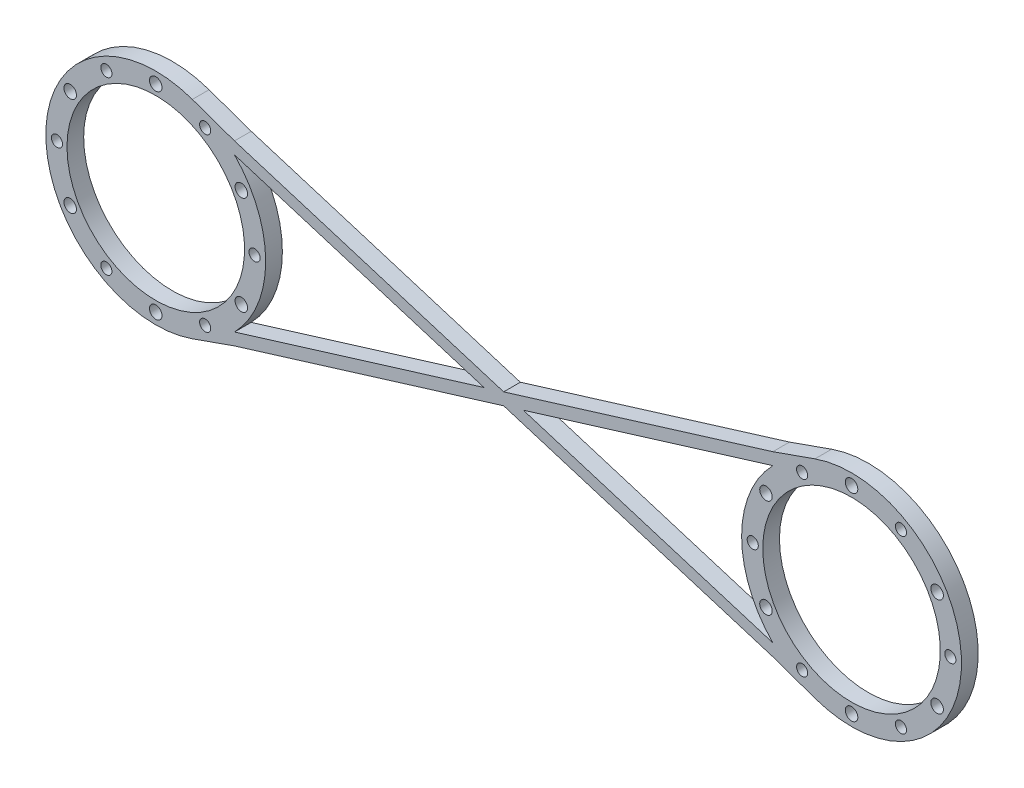
SolidWorks part; units mm, degrees
ref_plane "前视基准面" through (0, 0, 0) normal (0, 0, 1) x (1, 0, 0)
ref_plane "上视基准面" through (0, 0, 0) normal (0, 1, 0) x (1, 0, 0)
ref_plane "右视基准面" through (0, 0, 0) normal (1, 0, 0) x (0, 0, -1)
sketch "草图1" plane through (0, 0, 0) normal (0, 0, 1) x (1, 0, 0)
  line L0 (0, 0) -> (28, 0)
  line L1 (28, 0) -> (28, -56)
  line L2 (28, -56) -> (-28, -56)
  line L3 (-28, -56) -> (-28, 0)
  line L4 (-28, 0) -> (0, 0)
extrude "凸台-拉伸1" add sketch "草图1" along normal blind 8
sketch "草图2" plane through (0, 0, 0) normal (0, 0, -1) x (-1, 0, 0)
  circle A0 centre (-23.55, -4.45) radius 2.5
  circle A1 centre (23.55, -4.45) radius 2.5
  circle A2 centre (23.55, -51.55) radius 2.5
  circle A3 centre (-23.55, -51.55) radius 2.5
extrude "切除-拉伸1" cut sketch "草图2" against normal blind 8
sketch "草图3" plane through (0, 0, 0) normal (0, 0, -1) x (-1, 0, 0)
  circle A0 centre (0, -28) radius 15
extrude "切除-拉伸3" cut sketch "草图3" against normal blind 8
sketch "草图4" plane through (0, 0, 0) normal (0, 0, -1) x (-1, 0, 0)
  circle A0 centre (0, -28) radius 25
extrude "凸台-拉伸2" add sketch "草图4" along normal blind 8
sketch "草图6" plane through (0, 0, -8) normal (0, 0, -1) x (-1, 0, 0)
  circle A0 centre (0, -28) radius 15
extrude "切除-拉伸6" cut sketch "草图6" against normal blind 8
sketch "草图9" plane through (0, 0, -8) normal (0, 0, -1) x (-1, 0, 0)
  circle A0 centre (0, -28) radius 39.5
extrude "凸台-拉伸3" add sketch "草图9" along normal blind 8
sketch "草图10" plane through (0, 0, -16) normal (0, 0, -1) x (-1, 0, 0)
  circle A0 centre (0, -28) radius 15
extrude "切除-拉伸7" cut sketch "草图10" against normal blind 8
fillet "圆角3" radius 5 1 edges at (-28, 0, 4)
fillet "圆角4" radius 5 1 edges at (28, 0, 4)
fillet "圆角5" radius 5 1 edges at (28, -56, 4)
fillet "圆角6" radius 5 1 edges at (-28, -56, 4)
sketch "草图11" plane through (0, 0, -16) normal (0, 0, -1) x (-1, 0, 0)
  circle A0 centre (0, -28) radius 20
extrude "切除-拉伸9" cut sketch "草图11" against normal blind 188
sketch "草图12" plane through (0, 0, -16) normal (0, 0, -1) x (-1, 0, 0)
  circle A0 centre (0, 7.5) radius 2.25
  circle A1 centre (25.1023, -2.8977) radius 2.25
  circle A2 centre (35.5, -28) radius 2.25
  circle A3 centre (25.1023, -53.1023) radius 2.25
  circle A4 centre (0, -63.5) radius 2.25
  circle A5 centre (-25.1023, -53.1023) radius 2.25
  circle A6 centre (-35.5, -28) radius 2.25
  circle A7 centre (-25.1023, -2.8977) radius 2.25
  circle A8 centre (13.5853, 4.7977) radius 2
  circle A9 centre (32.7977, -14.4147) radius 2
  circle A10 centre (32.7977, -41.5853) radius 2
  circle A11 centre (13.5853, -60.7977) radius 2
  circle A12 centre (-13.5853, -60.7977) radius 2
  circle A13 centre (-32.7977, -41.5853) radius 2
  circle A14 centre (-32.7977, -14.4147) radius 2
  circle A15 centre (-13.5853, 4.7977) radius 2
extrude "切除-拉伸10" cut sketch "草图12" against normal blind 9
sketch "草图13" plane through (0, 0, 8) normal (0, 0, 1) x (1, 0, 0)
  circle A0 centre (-7.5178, -22.2915) radius 54.473
extrude "切除-拉伸11" cut sketch "草图13" against normal blind 2
sketch "草图14" plane through (0, 0, -16) normal (0, 0, -1) x (-1, 0, 0)
  circle A0 centre (0.9942, -28.0217) radius 59.1589
extrude "切除-拉伸12" cut sketch "草图14" against normal blind 2
sketch "草图15" plane through (0, 0, 6) normal (0, 0, 1) x (1, 0, 0)
  circle A0 centre (21.3873, -13.1283) radius 97.5442
extrude "切除-拉伸13" cut sketch "草图15" against normal up to surface (14 mm away) up to face at (-15.5853, 4.7977, -8)
sketch "草图16" plane through (0, 0, -14) normal (0, 0, -1) x (-1, 0, 0)
  circle A0 centre (0, -28) radius 31.9
extrude "切除-拉伸14" cut sketch "草图16" against normal blind 10
sketch "草图17" plane through (0, 0, -14) normal (0, 0, -1) x (-1, 0, 0)
  line L0 (0, -65.75) -> (0, -61.25)
  line L1 (0, -61.25) -> (2.25, -61.25)
  line L2 (2.25, -61.25) -> (2.25, -65.75)
  line L3 (2.25, -65.75) -> (0, -65.75)
  circle A0 centre (0, -63.5) radius 2.25 construction
extrude "凸台-拉伸4" add sketch "草图17" against normal blind 6
sketch "草图18" plane through (0, 0, 0) normal (1, 0, 0) x (0, 0, -1)
  line L1 (14, -61.25) -> (8, -61.25)
  line L2 (14, -61.25) -> (14, -65.75)
  line L3 (14, -65.75) -> (8, -65.75)
  line L4 (8, -61.25) -> (8, -65.75)
extrude "凸台-拉伸5" add sketch "草图18" along normal blind 200
sketch "草图19" plane through (0, 0, -14) normal (0, 0, -1) x (-1, 0, 0)
  line L0 (-200, -65.75) -> (-200, -67.5)
  line L1 (-200, -67.5) -> (-11.625, -67.5)
  line L2 (-11.625, -67.5) -> (0, -67.5)
  line L3 (0, -67.5) -> (0, -65.75)
  line L4 (0, -65.75) -> (-11.627, -65.75)
  line L5 (-11.627, -65.75) -> (-200, -65.75)
  arc A0 (-11.627, -65.75) -> (-21.3234, -61.25) centre (0, -28) ccw construction
extrude "凸台-拉伸6" add sketch "草图19" against normal blind 6
sketch "草图21" plane through (0, 0, -14) normal (0, 0, -1) x (-1, 0, 0)
  line L0 (-200, -61.25) -> (-200, -59.9)
  line L1 (-200, -59.9) -> (0, -59.9)
  line L2 (0, -59.9) -> (0, -61.25)
  line L3 (0, -61.25) -> (-200, -61.25)
  circle A0 centre (0, -28) radius 31.9 construction
extrude "凸台-拉伸7" add sketch "草图21" against normal blind 6
sketch "草图22" plane through (0, 0, -14) normal (0, 0, -1) x (-1, 0, 0)
  circle A0 centre (-223.2946, -28) radius 39.5
extrude "凸台-拉伸8" add sketch "草图22" against normal blind 6 separate body
sketch "草图23" plane through (0, 0, -14) normal (0, 0, -1) x (-1, 0, 0)
  circle A0 centre (-223.2946, -28) radius 31.9
extrude "切除-拉伸15" cut sketch "草图23" against normal blind 6
sketch "草图26" plane through (0, 0, -14) normal (0, 0, -1) x (-1, 0, 0)
  line L0 (-200, -59.9) -> (-223.2946, -59.9)
  line L1 (-223.2946, -59.9) -> (-223.2946, -67.5)
  line L2 (-223.2946, -67.5) -> (-200, -67.5)
  line L3 (-200, -67.5) -> (-200, -59.9)
  circle A0 centre (-223.2946, -28) radius 31.9 construction
  circle A1 centre (-223.2946, -28) radius 39.5 construction
extrude "凸台-拉伸9" add sketch "草图26" against normal blind 6
sketch "草图27" plane through (0, 0, -14) normal (0, 0, -1) x (-1, 0, 0)
  circle A0 centre (-223.2946, 7.5) radius 2.25
  circle A1 centre (-198.1923, -2.8977) radius 2.25
  circle A2 centre (-187.7946, -28) radius 2.25
  circle A3 centre (-198.1923, -53.1023) radius 2.25
  circle A4 centre (-223.2946, -63.5) radius 2.25
  circle A5 centre (-248.3969, -53.1023) radius 2.25
  circle A6 centre (-258.7946, -28) radius 2.25
  circle A7 centre (-248.3969, -2.8977) radius 2.25
  circle A8 centre (-209.7094, 4.7977) radius 2
  circle A9 centre (-190.4969, -14.4147) radius 2
  circle A10 centre (-190.4969, -41.5853) radius 2
  circle A11 centre (-209.7094, -60.7977) radius 2
  circle A12 centre (-236.8799, -60.7977) radius 2
  circle A13 centre (-256.0924, -41.5853) radius 2
  circle A14 centre (-256.0924, -14.4147) radius 2
  circle A15 centre (-236.8799, 4.7977) radius 2
extrude "切除-拉伸16" cut sketch "草图27" against normal blind 6
sketch "草图28" plane through (0, 0, -14) normal (0, 0, -1) x (-1, 0, 0)
  line L4 (-223.2946, 5.25) -> (-223.2946, 7.5)
  line L5 (-223.2946, 7.5) -> (-223.2946, 9.75)
  line L6 (-223.2946, 9.75) -> (-221.0446, 9.75)
  line L7 (-221.0446, 9.75) -> (-221.0446, 5.25)
  line L8 (-221.0446, 5.25) -> (-223.2946, 5.25)
  circle A4 centre (-223.2946, 7.5) radius 2.25 construction
extrude "凸台-拉伸10" add sketch "草图28" against normal blind 6
sketch "草图29" plane through (223.2946, 0, 0) normal (1, 0, 0) x (0, 0, -1)
  line L1 (14, 9.75) -> (8, 9.75)
  line L2 (14, 9.75) -> (14, 5.25)
  line L3 (14, 5.25) -> (8, 5.25)
  line L4 (8, 9.75) -> (8, 5.25)
extrude "凸台-拉伸11" add sketch "草图29" against normal blind 227
sketch "草图30" plane through (0, 0, -14) normal (0, 0, -1) x (-1, 0, 0)
  line L1 (-11.627, 11.5) -> (0, 11.5)
  line L2 (0, 11.5) -> (0, 9.75)
  line L3 (0, 9.75) -> (-223.2946, 9.75)
  line L4 (-223.2946, 9.75) -> (-223.2946, 11.5)
  line L5 (-223.2946, 11.5) -> (-11.627, 11.5)
  arc A0 (0, -67.5) -> (-11.627, 9.75) centre (0, -28) ccw construction
  arc A1 (-211.6676, 9.75) -> (-223.2946, -67.5) centre (-223.2946, -28) ccw construction
extrude "凸台-拉伸12" add sketch "草图30" against normal blind 6
sketch "草图31" plane through (0, 0, -14) normal (0, 0, -1) x (-1, 0, 0)
  line L0 (-201.9712, 5.25) -> (-201.9712, 3.9)
  line L1 (-201.9712, 3.9) -> (-9.5197, 3.9)
  line L2 (-9.5197, 3.9) -> (-9.5197, 5.25)
  line L3 (-9.5197, 5.25) -> (-201.9712, 5.25)
extrude "凸台-拉伸13" add sketch "草图31" against normal blind 6
sketch "草图32" plane through (0, 0, -14) normal (0, 0, -1) x (-1, 0, 0)
  circle A0 centre (-13.5853, 4.7977) radius 2
extrude "切除-拉伸17" cut sketch "草图32" against normal blind 6
sketch "草图33" plane through (0, 0, -14) normal (0, 0, -1) x (-1, 0, 0)
  circle A0 centre (0, 7.5) radius 2.25
extrude "切除-拉伸18" cut sketch "草图33" against normal blind 6
sketch "草图34" plane through (0, 0, -14) normal (0, 0, -1) x (-1, 0, 0)
  circle A0 centre (-13.5853, -60.7977) radius 2
extrude "切除-拉伸19" cut sketch "草图34" against normal blind 6
sketch "草图35" plane through (0, 0, -14) normal (0, 0, -1) x (-1, 0, 0)
  circle A0 centre (0, -63.5) radius 2.25
extrude "切除-拉伸20" cut sketch "草图35" against normal blind 6
sketch "草图36" plane through (0, 0, -14) normal (0, 0, -1) x (-1, 0, 0)
  circle A0 centre (-223.2946, 7.5) radius 2.25
  circle A1 centre (-209.7094, 4.7977) radius 2
extrude "切除-拉伸21" cut sketch "草图36" against normal blind 6
sketch "草图37" plane through (0, 0, -14) normal (0, 0, -1) x (-1, 0, 0)
  circle A0 centre (26.7054, -28) radius 39.5
extrude "凸台-拉伸14" add sketch "草图37" against normal blind 6 contours A0
sketch "草图38" plane through (0, 0, -14) normal (0, 0, -1) x (-1, 0, 0)
  circle A0 centre (26.7054, -28) radius 31.9
extrude "切除-拉伸22" cut sketch "草图38" against normal blind 6
sketch "草图39" plane through (0, 0, -14) normal (0, 0, -1) x (-1, 0, 0)
  line L0 (13.3527, 9.1747) -> (-4.9924, 19.1101)
  line L1 (-4.9924, 19.1101) -> (-56.4941, 19.1101)
  line L2 (-56.4941, 19.1101) -> (-56.4941, -75.9838)
  line L3 (-56.4941, -75.9838) -> (13.3527, -75.9838)
  line L4 (13.3527, -75.9838) -> (13.3527, -65.1747)
  arc A0 (13.3527, -65.1747) -> (13.3527, 9.1747) centre (26.7054, -28) cw
  arc A1 (13.3527, -65.1747) -> (13.3527, 9.1747) centre (26.7054, -28) ccw construction
extrude "切除-拉伸23" cut sketch "草图39" against normal blind 6
sketch "草图40" plane through (0, 0, -14) normal (0, 0, -1) x (-1, 0, 0)
  line L1 (-56.4941, 3.9) -> (26.7054, 3.9)
  line L2 (-56.4941, 3.9) -> (-56.4941, 11.5)
  line L3 (-56.4941, 11.5) -> (26.7054, 11.5)
  line L4 (26.7054, 3.9) -> (26.7054, 11.5)
  circle A0 centre (26.7054, -28) radius 39.5 construction
extrude "凸台-拉伸15" add sketch "草图40" against normal blind 6
sketch "草图41" plane through (0, 0, -14) normal (0, 0, -1) x (-1, 0, 0)
  line L1 (-56.4941, -59.9) -> (26.7054, -59.9)
  line L2 (-56.4941, -59.9) -> (-56.4941, -67.5)
  line L3 (-56.4941, -67.5) -> (26.7054, -67.5)
  line L4 (26.7054, -59.9) -> (26.7054, -67.5)
  arc A0 (3.4107, 3.9) -> (26.7054, 11.5) centre (26.7054, -28) ccw construction
extrude "凸台-拉伸16" add sketch "草图41" against normal blind 6
sketch "草图42" plane through (0, 0, -14) normal (0, 0, -1) x (-1, 0, 0)
  circle A0 centre (26.7054, -63.5) radius 2.25
  circle A1 centre (1.6031, -53.1023) radius 2.25
  circle A2 centre (-8.7946, -28) radius 2.25
  circle A3 centre (1.6031, -2.8977) radius 2.25
  circle A4 centre (26.7054, 7.5) radius 2.25
  circle A5 centre (51.8077, -2.8977) radius 2.25
  circle A6 centre (62.2054, -28) radius 2.25
  circle A7 centre (51.8077, -53.1023) radius 2.25
extrude "切除-拉伸24" cut sketch "草图42" against normal blind 6
sketch "草图43" plane through (0, 0, -14) normal (0, 0, -1) x (-1, 0, 0)
  circle A1 centre (13.1201, -60.7977) radius 2
  circle A2 centre (-6.0924, -41.5853) radius 2
  circle A3 centre (-6.0924, -14.4147) radius 2
  circle A4 centre (13.1201, 4.7977) radius 2
  circle A5 centre (40.2906, 4.7977) radius 2
  circle A6 centre (59.5031, -14.4147) radius 2
  circle A7 centre (59.5031, -41.5853) radius 2
  circle A8 centre (40.2906, -60.7977) radius 2
extrude "切除-拉伸25" cut sketch "草图43" against normal blind 6
sketch "草图45" plane through (0, 0, -14) normal (0, 0, -1) x (-1, 0, 0)
  line L0 (3.4107, 3.9) -> (-1.5893, 3.9)
  line L1 (-200, 3.9) -> (3.4107, 3.9) construction
  line L2 (3.4107, 3.9) -> (-0.3265, -0.2075)
  line L3 (-200, -59.9) -> (-195, -59.9)
  line L4 (3.4107, -59.9) -> (-200, -59.9) construction
  line L5 (-195, -59.9) -> (-1.5893, -0.438)
  line L6 (-1.5893, 3.9) -> (-195, -55.562)
  line L7 (-0.3265, -0.2075) -> (-1.5893, -0.438)
  line L8 (-200, -59.9) -> (-196.0531, -55.562)
  line L9 (-196.0531, -55.562) -> (-195, -55.562)
  arc A0 (3.4107, 3.9) -> (3.4107, -59.9) centre (26.7054, -28) ccw construction
  arc A1 (-200, -59.9) -> (-200, 3.9) centre (-223.2946, -28) ccw construction
extrude "凸台-拉伸17" add sketch "草图45" against normal blind 6
sketch "草图46" plane through (0, 0, -14) normal (0, 0, -1) x (-1, 0, 0)
  line L0 (3.4107, -59.9) -> (-1.5893, -59.9)
  line L1 (3.4107, -59.9) -> (-195, -59.9) construction
  line L2 (-1.5893, -55.562) -> (3.4107, -56.6542)
  line L3 (-200, 3.9) -> (-195, 3.9)
  line L4 (-200, 3.9) -> (-1.5893, 3.9) construction
  line L6 (-195, 3.9) -> (-1.5893, -55.562)
  line L7 (3.4107, -56.6542) -> (3.4107, -59.9)
  line L8 (-1.5893, -59.9) -> (-195, -0.438)
  line L9 (-195, -0.438) -> (-198.2205, 0.6383)
  line L10 (-198.2205, 0.6383) -> (-200, 3.9)
  arc A0 (-1.5893, -0.438) -> (3.4107, -59.9) centre (26.7054, -28) ccw construction
  arc A1 (-195, -55.562) -> (-200, 3.9) centre (-223.2946, -28) ccw construction
extrude "凸台-拉伸18" add sketch "草图46" against normal blind 6
sketch "草图48" plane through (0, 0, -14) normal (0, 0, -1) x (-1, 0, 0)
  line L0 (-195, 3.9) -> (-200, 3.9)
  line L1 (-223.2946, 11.5) -> (26.7054, 11.5)
  line L2 (-195, 3.9) -> (3.4107, 3.9)
  arc A0 (-223.2946, 11.5) -> (-200, 3.9) centre (-223.2946, -28) cw
  arc A1 (-223.2946, 11.5) -> (-223.2946, -67.5) centre (-223.2946, -28) ccw construction
  arc A2 (26.7054, -67.5) -> (26.7054, 11.5) centre (26.7054, -28) ccw construction
  arc A3 (26.7054, 11.5) -> (3.4107, 3.9) centre (26.7054, -28) ccw
extrude "切除-拉伸26" cut sketch "草图48" against normal blind 10
sketch "草图49" plane through (0, 0, -14) normal (0, 0, -1) x (-1, 0, 0)
  line L2 (-195, 3.9) -> (-210.1446, 9.2468)
  line L3 (-210.1446, 9.2468) -> (-203.4289, 3.9)
  line L4 (-203.4289, 3.9) -> (-195.6872, 2.185)
  line L5 (-195.6872, 2.185) -> (-195, 3.9)
  arc A0 (-200, 3.9) -> (-223.2946, -67.5) centre (-223.2946, -28) ccw construction
extrude "凸台-拉伸19" add sketch "草图49" against normal blind 6
sketch "草图50" plane through (0, 0, -14) normal (0, 0, -1) x (-1, 0, 0)
  line L0 (-1.5893, 3.9) -> (13.5553, 9.2468)
  line L1 (13.5553, 9.2468) -> (12.4845, 7.0073)
  line L2 (12.4845, 7.0073) -> (5.1657, 2.1435)
  line L3 (5.1657, 2.1435) -> (-1.5893, 3.9)
  arc A0 (26.7054, -67.5) -> (3.4107, 3.9) centre (26.7054, -28) ccw construction
extrude "凸台-拉伸20" add sketch "草图50" against normal blind 6
sketch "草图51" plane through (0, 0, -14) normal (0, 0, -1) x (-1, 0, 0)
  line L0 (-195, -59.9) -> (-200, -59.9)
  line L1 (-223.2946, -67.5) -> (26.7054, -67.5)
  line L2 (-195, -59.9) -> (3.4107, -59.9)
  arc A0 (-223.2946, -67.5) -> (-200, -59.9) centre (-223.2946, -28) ccw
  arc A1 (26.7054, -67.5) -> (3.4107, -59.9) centre (26.7054, -28) cw
extrude "切除-拉伸27" cut sketch "草图51" against normal blind 6
sketch "草图52" plane through (0, 0, -14) normal (0, 0, -1) x (-1, 0, 0)
  line L0 (-195, -59.9) -> (-210.1445, -65.2468)
  line L1 (-210.1445, -65.2468) -> (-210.1445, -63.8332)
  line L2 (-210.1445, -63.8332) -> (-204.4488, -59.9)
  line L3 (-204.4488, -59.9) -> (-198.0565, -58.8983)
  line L4 (-198.0565, -58.8983) -> (-195, -59.9)
  arc A0 (-210.1446, 9.2468) -> (-200, -59.9) centre (-223.2946, -28) ccw construction
extrude "凸台-拉伸21" add sketch "草图52" against normal blind 6
sketch "草图53" plane through (0, 0, -14) normal (0, 0, -1) x (-1, 0, 0)
  line L0 (-1.5893, -59.9) -> (13.5553, -65.2468)
  line L1 (13.5553, -65.2468) -> (13.9521, -64.123)
  line L2 (13.9521, -64.123) -> (8.197, -60.9763)
  line L3 (8.197, -60.9763) -> (3.9989, -56.8743)
  line L4 (3.9989, -56.8743) -> (-1.5893, -59.9)
  arc A0 (3.4107, -59.9) -> (13.5553, 9.2468) centre (26.7054, -28) ccw construction
extrude "凸台-拉伸22" add sketch "草图53" against normal blind 6
sketch "草图54" plane through (0, 0, -14) normal (0, 0, -1) x (-1, 0, 0)
  circle A0 centre (-209.6769, 5.5627) radius 3.0231
  circle A1 centre (-198.1923, -2.8977) radius 3.0875
  circle A2 centre (-190.1676, -13.9578) radius 3.1216
  circle A3 centre (-190.4969, -41.5853) radius 2.9928
  circle A4 centre (-198.1923, -53.1023) radius 3.413
  circle A5 centre (-209.7094, -60.6149) radius 2.5956
  circle A6 centre (-236.8799, -60.7977) radius 3.0205
  circle A7 centre (-248.3969, -53.1023) radius 2.9818
  circle A8 centre (-256.0924, -41.5853) radius 2.6235
  circle A9 centre (-256.0924, -14.4147) radius 2.955
  circle A10 centre (-248.3969, -2.8977) radius 2.9208
  circle A11 centre (-236.8799, 4.7977) radius 2.881
extrude "凸台-拉伸26" add sketch "草图54" against normal blind 6
sketch "草图55" plane through (0, 0, -14) normal (0, 0, -1) x (-1, 0, 0)
  circle A0 centre (-205.5446, 2.7439) radius 2
  circle A1 centre (-192.5507, -10.25) radius 2.25
  circle A2 centre (-192.5507, -45.75) radius 2.25
  circle A3 centre (-205.5446, -58.7439) radius 2
  circle A4 centre (-241.0446, -58.7439) radius 2
  circle A5 centre (-254.0385, -45.75) radius 2.25
  circle A6 centre (-254.0385, -10.25) radius 2.25
  circle A7 centre (-241.0446, 2.7439) radius 2
extrude "切除-拉伸28" cut sketch "草图55" against normal blind 6
sketch "草图56" plane through (0, 0, -14) normal (0, 0, -1) x (-1, 0, 0)
  circle A0 centre (-187.8811, -28.1211) radius 3.1332
extrude "凸台-拉伸27" add sketch "草图56" against normal blind 6
sketch "草图57" plane through (0, 0, -14) normal (0, 0, -1) x (-1, 0, 0)
  circle A0 centre (-187.7946, -28) radius 2
extrude "切除-拉伸29" cut sketch "草图57" against normal blind 6
sketch "草图58" plane through (0, 0, -14) normal (0, 0, -1) x (-1, 0, 0)
  circle A0 centre (-258.7946, -28) radius 3.3937
extrude "凸台-拉伸28" add sketch "草图58" against normal blind 6
sketch "草图59" plane through (0, 0, -14) normal (0, 0, -1) x (-1, 0, 0)
  circle A0 centre (-258.7946, -28) radius 2
extrude "切除-拉伸30" cut sketch "草图59" against normal blind 6
sketch "草图60" plane through (0, 0, -14) normal (0, 0, -1) x (-1, 0, 0)
  circle A0 centre (40.3304, 4.9308) radius 3.1965
  circle A1 centre (51.8077, -2.8977) radius 3.1855
  circle A2 centre (59.5031, -14.4147) radius 2.8935
  circle A3 centre (59.5031, -41.5853) radius 3.1239
  circle A4 centre (51.8077, -53.1023) radius 3.1904
  circle A5 centre (40.2906, -60.7977) radius 2.8763
  circle A6 centre (13.1201, -60.7977) radius 2.9853
  circle A7 centre (1.6031, -53.1023) radius 3.1655
  circle A8 centre (-6.0924, -41.5853) radius 2.9698
  circle A9 centre (-6.0924, -14.4147) radius 2.731
  circle A10 centre (1.6031, -2.8977) radius 2.7477
  circle A11 centre (13.1201, 4.7977) radius 2
extrude "凸台-拉伸29" add sketch "草图60" against normal blind 6
sketch "草图61" plane through (0, 0, -14) normal (0, 0, -1) x (-1, 0, 0)
  circle A0 centre (62.2054, -28) radius 3.1465
  circle A1 centre (-8.7946, -28) radius 3.0365
extrude "凸台-拉伸30" add sketch "草图61" against normal blind 6
sketch "草图62" plane through (0, 0, -14) normal (0, 0, -1) x (-1, 0, 0)
  circle A0 centre (44.4554, 2.7439) radius 2
  circle A1 centre (62.2054, -28) radius 2
  circle A2 centre (44.4554, -58.7439) radius 2
  circle A3 centre (8.9554, -58.7439) radius 2
  circle A4 centre (-8.7946, -28) radius 2
  circle A5 centre (8.9554, 2.7439) radius 2
  circle A6 centre (57.4493, -10.25) radius 2.25
  circle A7 centre (57.4493, -45.75) radius 2.25
  circle A8 centre (-4.0385, -45.75) radius 2.25
  circle A9 centre (-4.0385, -10.25) radius 2.25
extrude "切除-拉伸31" cut sketch "草图62" against normal blind 6
